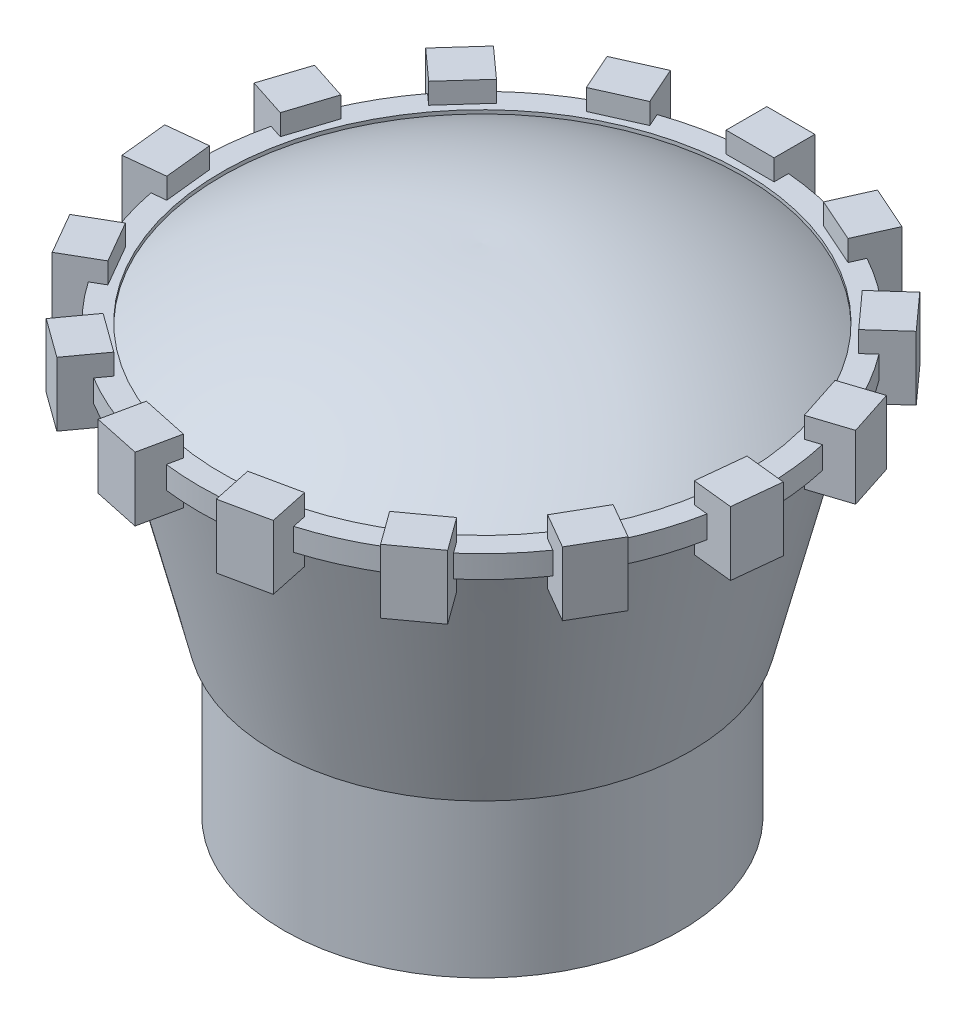
SolidWorks part; units mm, degrees
material "PLA"
ref_plane "Front Plane" through (0, 0, 0) normal (0, 0, 1) x (1, 0, 0)
ref_plane "Top Plane" through (0, 0, 0) normal (0, 1, 0) x (1, 0, 0)
ref_plane "Right Plane" through (0, 0, 0) normal (1, 0, 0) x (0, 0, -1)
sketch "Sketch1" plane through (0, 0, 0) normal (0, 1, 0) x (1, 0, 0)
  circle A0 centre (0, 0) radius 6.5
  dimension "D1" = 13
extrude "Boss-Extrude1" add sketch "Sketch1" along normal blind 8 draft 14 contours A0 draft outward yes
sketch "Sketch2" plane through (0, 0, 0) normal (0, -1, 0) x (1, 0, 0)
  circle A0 centre (0, 0) radius 6.2
  dimension "D1" = 12.4
extrude "Boss-Extrude2" add sketch "Sketch2" along normal blind 5 contours A0
sketch "Sketch3" plane through (0, -5, 0) normal (0, -1, 0) x (1, 0, 0)
  circle A0 centre (0, 0) radius 5.75
  dimension "D1" = 11.5
extrude "Cut-Extrude1" cut sketch "Sketch3" against normal blind 5 contours A0
sketch "Sketch4" plane through (0, 0, 0) normal (1, 0, 0) x (0, 0, -1)
  line L0 (0, 8) -> (0, 10.5)
  line L1 (8.4946, 8) -> (-8.4946, 8) construction
  line L2 (0, 7.15) -> (0, -7.15) construction
  line L3 (0, 8) -> (8.4946, 8)
  spline S0 degree 2 poles (0, 10.5) (4.6166, 10.6897) (8.4946, 8) knots 0 0 0 1 1 1
  dimension "D1" = 3.5345
  dimension "D2" = 10.2
  dimension "D3" = 10.5
revolve "Revolve1" add sketch "Sketch4" angle 360 about L0
sketch "Sketch5" plane through (0, 0, 0) normal (1, 0, 0) x (0, 0, -1)
  line L0 (-8.4946, 8) -> (8.4946, 8) construction
  line L1 (8.1446, 8.35) -> (8.8446, 8.35)
  line L2 (8.1446, 8.35) -> (8.1446, 7.65)
  line L3 (8.1446, 7.65) -> (8.8446, 7.65)
  line L4 (8.8446, 8.35) -> (8.8446, 7.65)
  line L5 (8.1446, 8.35) -> (8.8446, 7.65) construction
  line L6 (8.1446, 7.65) -> (8.8446, 8.35) construction
  point P0 (8.4946, 8)
  dimension "D1" = 0.7
  dimension "D2" = 0.7
ref_axis "Axis1" through (0, -5.7485, 0) along (0, 1, 0)
revolve "Revolve2" add sketch "Sketch5" angle 360 about axis through (0, -5.7485, 0) along (0, 1, 0)
sketch "Sketch6" plane through (0, 0, 0) normal (1, 0, 0) x (0, 0, -1)
  line L1 (8.3634, 9) -> (9.6366, 9)
  line L2 (8.3634, 9) -> (8.3634, 7)
  line L3 (8.3634, 7) -> (9.6366, 7)
  line L4 (9.6366, 9) -> (9.6366, 7)
  line L5 (8.3634, 9) -> (9.6366, 7) construction
  line L6 (8.3634, 7) -> (9.6366, 9) construction
  point P0 (9, 8)
  dimension "D1" = 2
  dimension "D2" = 9
  dimension "D3" = 8
  dimension "D4" = 9.6366
extrude "Boss-Extrude4" add sketch "Sketch6" along normal mid plane 1.5 contours L4 L3 L2 L1
pattern_circular "CirPattern1" count 15 over 360 about axis through (0, 0, 0) along (0, 1, 0) of "Boss-Extrude4"
